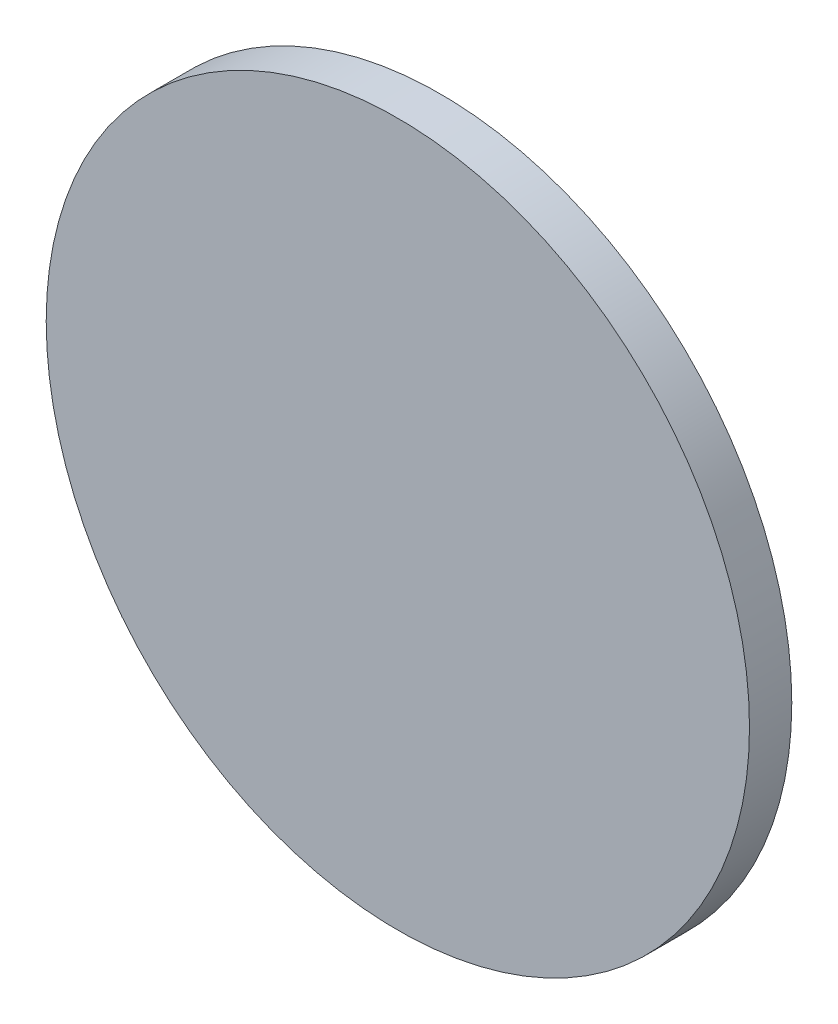
SolidWorks part; units mm, degrees
ref_plane "前视基准面" through (0, 0, 0) normal (0, 0, 1) x (1, 0, 0)
ref_plane "上视基准面" through (0, 0, 0) normal (0, 1, 0) x (1, 0, 0)
ref_plane "右视基准面" through (0, 0, 0) normal (1, 0, 0) x (0, 0, -1)
sketch "草图1" plane through (0, 0, 0) normal (0, 0, 1) x (1, 0, 0)
  circle A0 centre (-0.3648, -188.0005) radius 24.9346
extrude "凸台-拉伸1" add sketch "草图1" along normal blind 3
